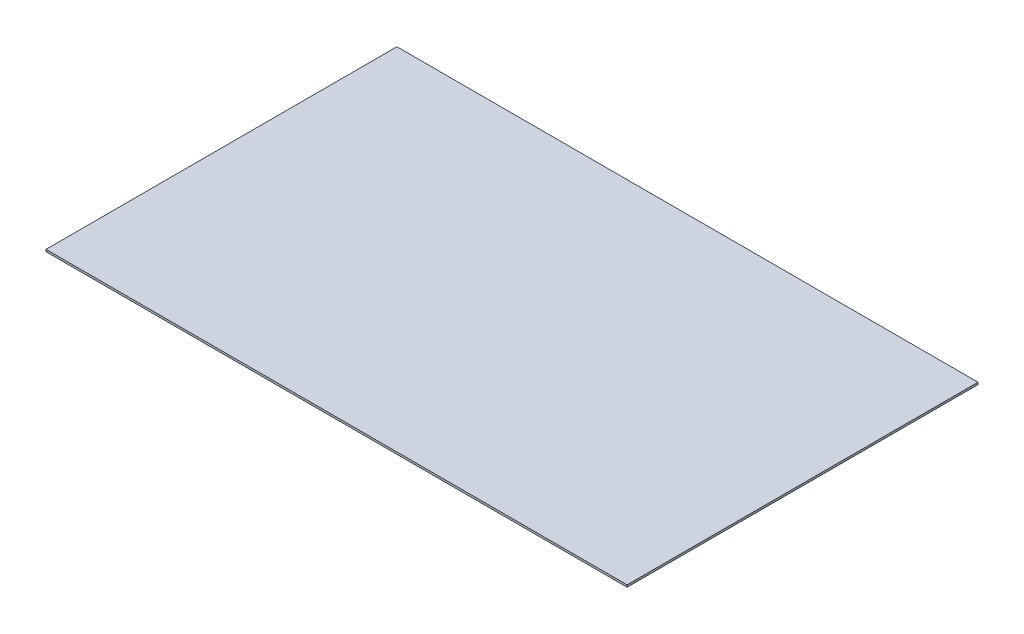
SolidWorks part; units mm, degrees
ref_plane "Front Plane" through (0, 0, 0) normal (0, 0, 1) x (1, 0, 0)
ref_plane "Top Plane" through (0, 0, 0) normal (0, 1, 0) x (1, 0, 0)
ref_plane "Right Plane" through (0, 0, 0) normal (1, 0, 0) x (0, 0, -1)
sketch "Sketch1" plane through (0, 0, 0) normal (0, 1, 0) x (1, 0, 0)
  line L1 (0, 0) -> (-828, 0)
  line L2 (0, 0) -> (0, -500)
  line L3 (0, -500) -> (-828, -500)
  line L4 (-828, 0) -> (-828, -500)
  dimension "D1" = 828
  dimension "D2" = 500
extrude "Boss-Extrude1" add sketch "Sketch1" along normal blind 3
